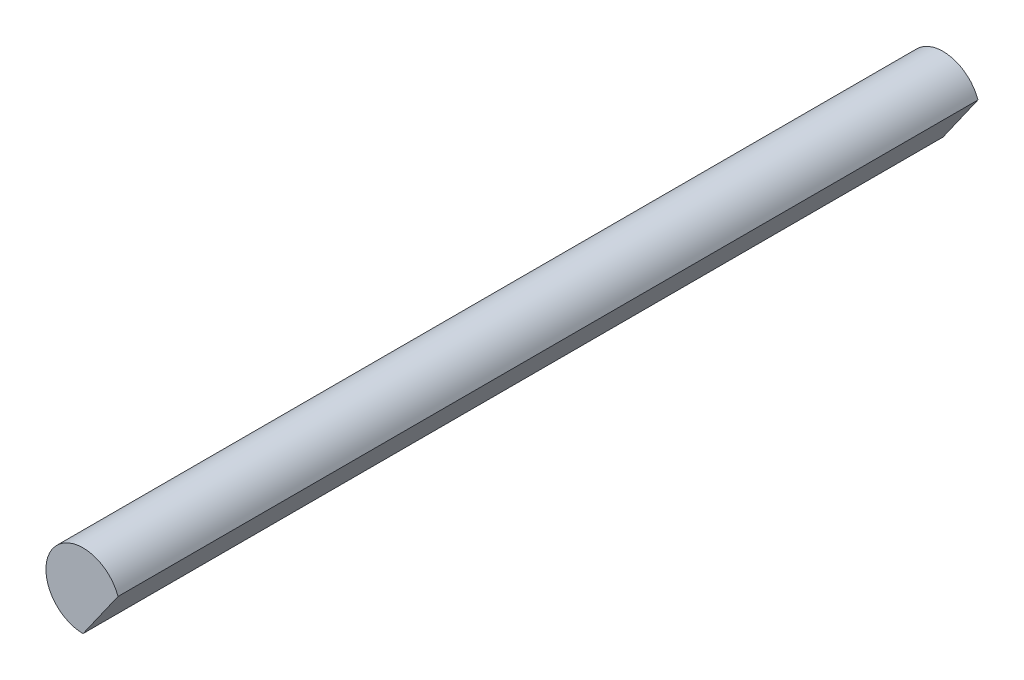
SolidWorks part; units mm, degrees
material "1060 Alloy"
ref_plane "Front Plane" through (0, 0, 0) normal (0, 0, 1) x (1, 0, 0)
ref_plane "Top Plane" through (0, 0, 0) normal (0, 1, 0) x (1, 0, 0)
ref_plane "Right Plane" through (0, 0, 0) normal (1, 0, 0) x (0, 0, -1)
sketch "Sketch1" plane through (0, 0, 0) normal (0, 0, 1) x (1, 0, 0)
  line L2 (-0.0017, -1.5) -> (1.4119, 0.5065)
  arc A2 (1.4119, 0.5065) -> (-0.0017, -1.5) centre (0, 0) ccw
extrude "Boss-Extrude1" add sketch "Sketch1" along normal up to surface (34.74 mm away)
